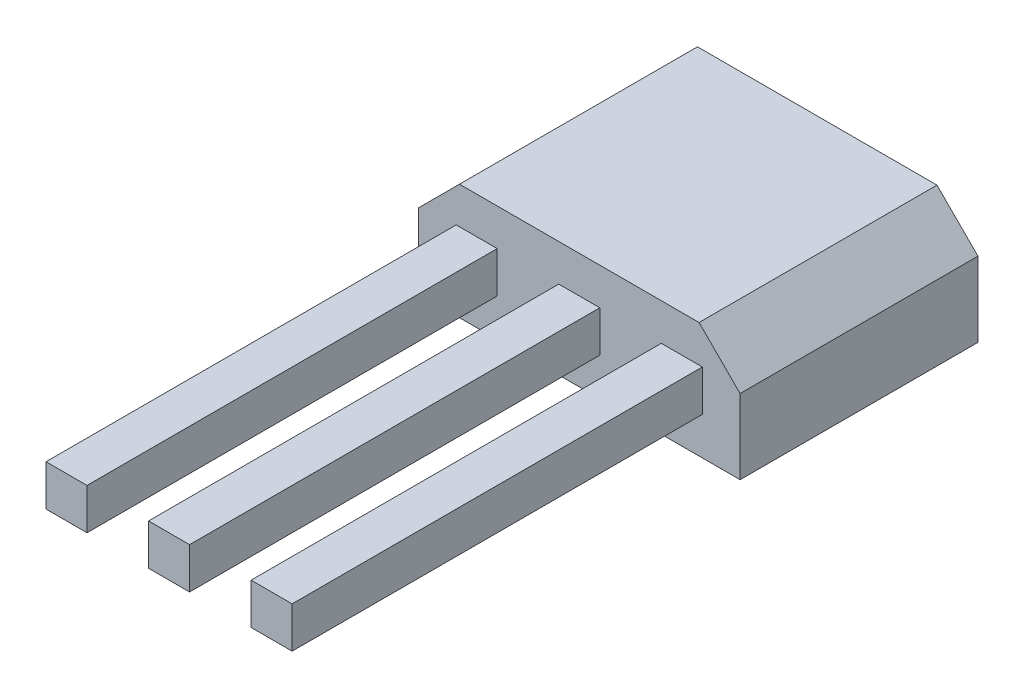
SolidWorks part; units mm, degrees
ref_plane "Front Plane" through (0, 0, 0) normal (0, 0, 1) x (1, 0, 0)
ref_plane "Top Plane" through (0, 0, 0) normal (0, 1, 0) x (1, 0, 0)
ref_plane "Right Plane" through (0, 0, 0) normal (1, 0, 0) x (0, 0, -1)
sketch "Sketch1" plane through (0, 0, 0) normal (0, 1, 0) x (1, 0, 0)
  line L1 (0, 0) -> (3.92, 0)
  line L2 (0, 0) -> (0, 2.9)
  line L3 (0, 2.9) -> (3.92, 2.9)
  line L4 (3.92, 0) -> (3.92, 2.9)
  dimension "D1" = 3.92
  dimension "D2" = 2.9
extrude "Boss-Extrude1" add sketch "Sketch1" along normal blind 1.41
chamfer "Chamfer1" distance 0.5 angle 45 2 edges at (0, 1.41, -1.45) (3.92, 1.41, -1.45)
sketch "Sketch2" plane through (0, 0, 0) normal (0, 0, 1) x (1, 0, 0)
  line L0 (0, 0.91) -> (0, 0) construction
  line L1 (0.46, 0.96) -> (0.96, 0.96)
  line L2 (0.46, 0.96) -> (0.46, 0.46)
  line L3 (0.46, 0.46) -> (0.96, 0.46)
  line L4 (0.96, 0.96) -> (0.96, 0.46)
  line L5 (1.71, 0.96) -> (2.21, 0.96)
  line L6 (1.71, 0.96) -> (1.71, 0.46)
  line L7 (1.71, 0.46) -> (2.21, 0.46)
  line L8 (2.21, 0.96) -> (2.21, 0.46)
  line L9 (2.96, 0.96) -> (3.46, 0.96)
  line L10 (2.96, 0.96) -> (2.96, 0.46)
  line L11 (2.96, 0.46) -> (3.46, 0.46)
  line L12 (3.46, 0.96) -> (3.46, 0.46)
  line L13 (3.92, 0.91) -> (3.92, 0) construction
  line L14 (0, 0) -> (3.92, 0) construction
  point P12 (0.96, 0.71)
  dimension "D1" = 0.5
  dimension "D2" = 0.5
  dimension "D3" = 0.5
  dimension "D4" = 0.5
  dimension "D5" = 0.5
  dimension "D6" = 0.5
  dimension "D7" = 0.75
  dimension "D8" = 0.75
  dimension "D9" = 0
  dimension "D10" = 0.46
  dimension "D11" = 0.46
  dimension "D12" = 0.46
extrude "Boss-Extrude2" add sketch "Sketch2" along normal blind 5
sketch "Sketch3" plane through (0, 1.41, 0) normal (0, 1, 0) x (1, 0, 0)
  line L0 (1.96, 2.9) -> (1.96, 0)
  line L1 (3.42, 2.9) -> (0.5, 2.9) construction
  line L2 (2.21, 0) -> (1.71, 0) construction
  circle A0 centre (1.96, 1.45) radius 1.45
